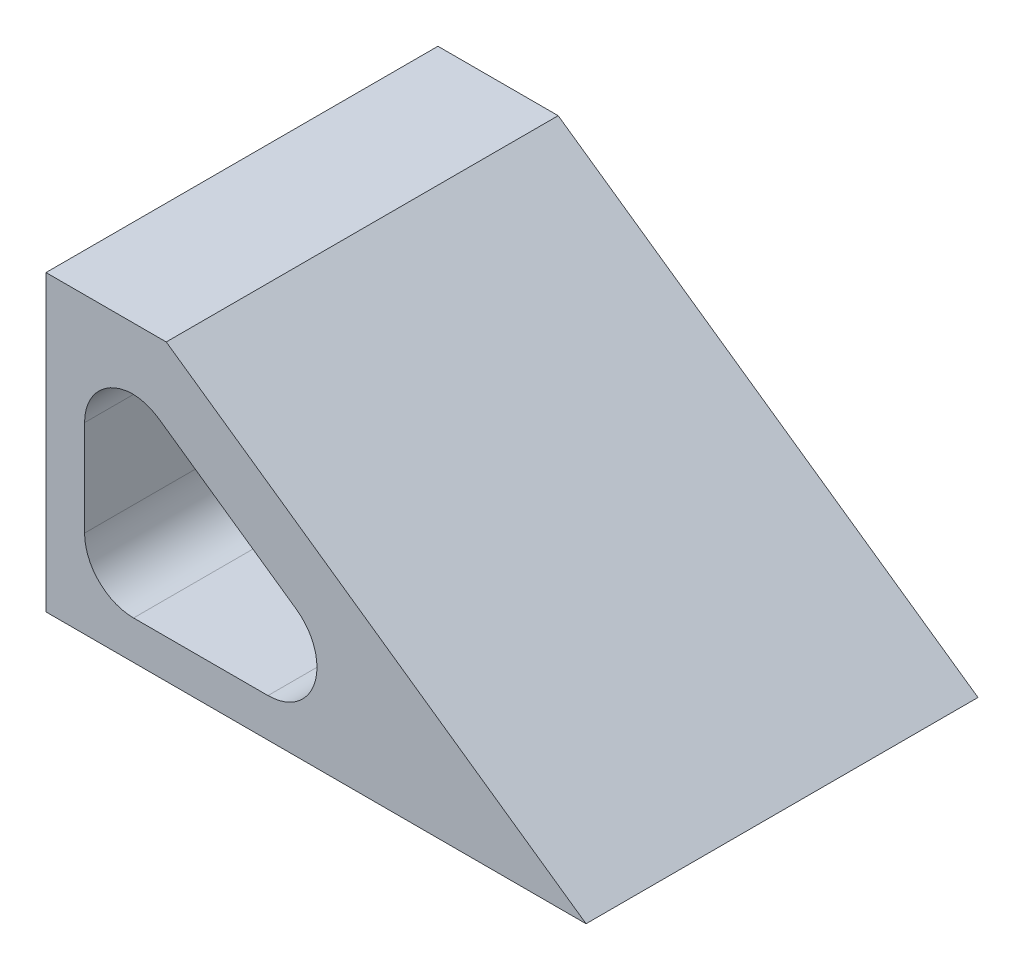
SolidWorks part; units mm, degrees
material "Nailon 101"
ref_plane "Alzado" through (0, 0, 0) normal (0, 0, 1) x (1, 0, 0)
ref_plane "Planta" through (0, 0, 0) normal (0, 1, 0) x (1, 0, 0)
ref_plane "Vista lateral" through (0, 0, 0) normal (1, 0, 0) x (0, 0, -1)
sketch "Croquis1" plane through (0, 0, 0) normal (0, 1, 0) x (1, 0, 0)
  line L0 (0, 25.4) -> (0, -25.4)
  line L1 (0, -25.4) -> (70, -25.4)
  line L2 (70, -25.4) -> (70, 25.4)
  line L3 (70, 25.4) -> (0, 25.4)
  dimension "D1" = 50.8
  dimension "D2" = 70
extrude "Saliente-Extruir1" add sketch "Croquis1" along normal blind 38.1
sketch "Croquis2" plane through (0, 0, 25.4) normal (0, 0, 1) x (1, 0, 0)
  line L0 (70, 0) -> (15.5876, 38.1)
  line L1 (0, 38.1) -> (70, 38.1) construction
  line L2 (15.5876, 38.1) -> (70, 38.1)
  line L3 (70, 38.1) -> (70, 0) construction
  line L4 (70, 0) -> (70, 38.1)
  dimension "D1" = 55
extrude "Cortar-Extruir5" cut sketch "Croquis2" against normal through all
sketch "Croquis3" plane through (0, 0, 25.4) normal (0, 0, 1) x (1, 0, 0)
  line L0 (5, 23.75) -> (5, 11.35)
  line L1 (11.35, 5) -> (28.7721, 5)
  line L2 (32.4143, 16.5516) -> (14.7052, 28.9516)
  line L3 (11.063, 30.1) -> (11.35, 30.1)
  line L4 (15.5876, 38.1) -> (70, 0) construction
  line L5 (0, 38.1) -> (0, 0) construction
  line L6 (0, 38.1) -> (15.5876, 38.1) construction
  line L7 (0, 0) -> (70, 0) construction
  arc A0 (28.7721, 5) -> (32.4143, 16.5516) centre (28.7721, 11.35) ccw
  arc A1 (14.7052, 28.9516) -> (11.063, 30.1) centre (11.063, 23.75) ccw
  arc A2 (5, 23.75) -> (11.35, 30.1) centre (11.35, 23.75) cw
  arc A3 (5, 11.35) -> (11.35, 5) centre (11.35, 11.35) ccw
  dimension "D1" = 6.35
  dimension "D2" = 5
  dimension "D3" = 8
  dimension "D4" = 5
  dimension "D5" = 8
extrude "Cortar-Extruir6" cut sketch "Croquis3" against normal through all contours L0 A3 L1 A0 L2 A1 A2
